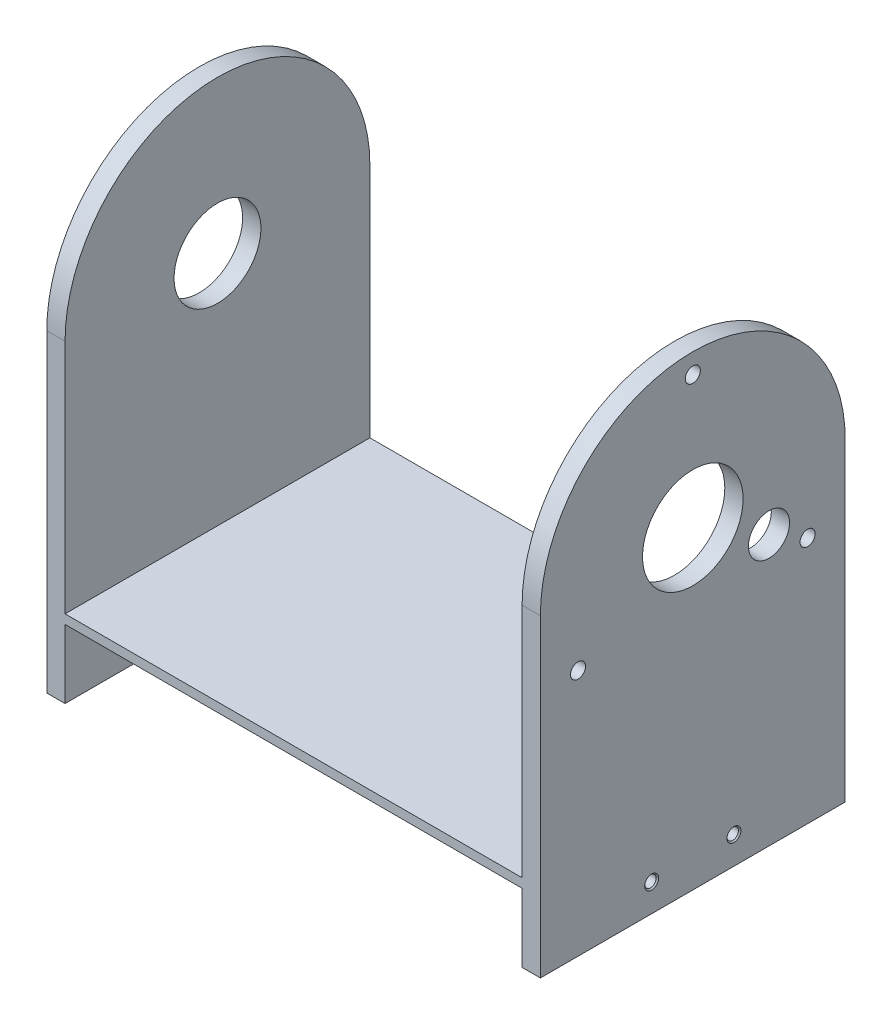
SolidWorks part; units mm, degrees
material "A-玻璃纤维"
ref_plane "前视基准面" through (0, 0, 0) normal (0, 0, 1) x (1, 0, 0)
ref_plane "上视基准面" through (0, 0, 0) normal (0, 1, 0) x (1, 0, 0)
ref_plane "右视基准面" through (0, 0, 0) normal (1, 0, 0) x (0, 0, -1)
sketch "草图1" plane through (0, 0, 0) normal (0, 1, 0) x (1, 0, 0)
  line L1 (-20, -33.35) -> (20, -33.35)
  line L2 (-20, -33.35) -> (-20, 33.35)
  line L3 (-20, 33.35) -> (20, 33.35)
  line L4 (20, -33.35) -> (20, 33.35)
  line L5 (-20, -33.35) -> (20, 33.35) construction
  line L6 (-20, 33.35) -> (20, -33.35) construction
  point P0 (0, 0)
  dimension "D1" = 40
  dimension "D2" = 66.7
extrude "凸台-拉伸1" add sketch "草图1" along normal blind 2
sketch "草图2" plane through (0, 2, 0) normal (0, 1, 0) x (1, 0, 0)
  line L0 (-20, -33.35) -> (20, -33.35) construction
  line L1 (-20, 33.35) -> (-16, 33.35)
  line L2 (-20, 33.35) -> (-20, -33.35)
  line L3 (-20, -33.35) -> (-16, -33.35)
  line L4 (-16, 33.35) -> (-16, -33.35)
  dimension "D1" = 4
extrude "凸台-拉伸2" add sketch "草图2" along normal blind 100
sketch "草图5" plane through (-20, 0, 0) normal (-1, 0, 0) x (0, 0, 1)
  line L0 (33.35, 102) -> (33.35, 0) construction
  line L1 (-33.35, 102) -> (33.35, 102) construction
  line L2 (33.35, 68.65) -> (33.35, 102)
  line L3 (33.35, 102) -> (0, 102)
  line L4 (0, 102) -> (-33.35, 102)
  line L5 (-33.35, 102) -> (-33.35, 68.65)
  circle A0 centre (0, 68.65) radius 33.35
  line M3 (33.35, 0) -> (33.35, 102)
  line M4 (33.35, 102) -> (-33.35, 102)
  line M5 (-33.35, 102) -> (-33.35, 0)
  dimension "D1" = 66.7
extrude "切除-拉伸1" cut sketch "草图5" against normal through all and the other way through all contours A0 M4 M5 | A0 M3 M4 | L2 L3 L4 L5
sketch "草图6" plane through (-20, 0, 0) normal (-1, 0, 0) x (0, 0, 1)
  line L0 (0, 68.65) -> (0, 97.65) construction
  line L1 (0, 68.65) -> (25.1147, 54.15) construction
  line L2 (0, 68.65) -> (-25.1147, 54.15) construction
  circle A0 centre (0, 68.65) radius 29 construction
  point P7 (0, 97.65)
  point P8 (25.1147, 54.15)
  point P9 (-25.1147, 54.15)
  point P10 (0, 68.65)
  dimension "D1" = 58
  dimension "D2" = 120
  dimension "D3" = 120
hole_wizard "M4 螺纹孔1" positions "草图7" profile "草图8" tap size "M4" standard "GB" end condition through all
sketch "草图7" plane through (-20, 0, 0) normal (-1, 0, 0) x (0, 0, 1)
  point P0 (0, 97.65)
  point P3 (25.1147, 54.15)
  point P6 (-25.1147, 54.15)
sketch "草图8" plane through (-20, 97.65, 0) normal (0, 1, 0) x (0, 0, 1)
  line L0 (0, 0) -> (0, 40)
  line L1 (0, 40) -> (1.65, 40)
  line L2 (1.65, 40) -> (1.65, 0.375)
  line L3 (1.65, 0.375) -> (2.025, 0)
  line L5 (2.025, 0) -> (0, 0)
  line L6 (-1.65, 0.375) -> (-2.025, 0) construction
  line L11 (0, -6.35) -> (0, 107.95) construction
  dimension "通孔螺纹孔钻头直径" = 3.3
  dimension "通孔螺纹孔钻头深度" = 40
  dimension "近端锥形沉头孔直径" = 4.05
  dimension "近端锥形沉头孔角度" = 90
sketch "草图9" plane through (0, 2, 0) normal (0, 1, 0) x (1, 0, 0)
  line L0 (-16, -33.35) -> (20, -33.35) construction
  line L1 (-11, 28.35) -> (15, 28.35) construction
  line L2 (-11, 28.35) -> (-11, -28.35) construction
  line L3 (-11, -28.35) -> (15, -28.35) construction
  line L4 (15, 28.35) -> (15, -28.35) construction
  line L5 (20, 33.35) -> (-16, 33.35) construction
  line L6 (20, -33.35) -> (20, 33.35) construction
  line L7 (-16, -33.35) -> (-16, 33.35) construction
  point P12 (-50.2188, 7.1013)
  point P13 (-11, 28.35)
  point P14 (-11, -28.35)
  point P15 (15, -28.35)
  point P16 (15, 28.35)
  dimension "D1" = 5
  dimension "D2" = 5
  dimension "D3" = 5
  dimension "D4" = 5
hole_wizard "M4 螺纹孔2" positions "草图9" profile "草图10" tap size "M4" standard "GB" end condition through all
sketch "草图10" plane through (15, 2, -28.35) normal (1, 0, 0) x (0, 0, 1)
  line L0 (0, 0) -> (0, 2)
  line L1 (0, 2) -> (1.65, 2)
  line L2 (1.65, 2) -> (1.65, 0.375)
  line L3 (1.65, 0.375) -> (2.025, 0)
  line L5 (2.025, 0) -> (0, 0)
  line L6 (-1.65, 0.375) -> (-2.025, 0) construction
  line L11 (0, -6.35) -> (0, 107.95) construction
  dimension "通孔螺纹孔钻头直径" = 3.3
  dimension "通孔螺纹孔钻头深度" = 2
  dimension "近端锥形沉头孔直径" = 4.05
  dimension "近端锥形沉头孔角度" = 90
sketch "草图11" plane through (-20, 0, 0) normal (-1, 0, 0) x (0, 0, 1)
  line L0 (-33.35, 68.65) -> (-33.35, 0) construction
  line L1 (-33.35, 17) -> (33.35, 17)
  line L2 (-33.35, 17) -> (-33.35, 15)
  line L3 (-33.35, 15) -> (33.35, 15)
  line L4 (33.35, 17) -> (33.35, 15)
  line L5 (33.35, 68.65) -> (33.35, 0) construction
  line L6 (-33.35, 0) -> (33.35, 0) construction
  dimension "D1" = 2
  dimension "D2" = 15
extrude "凸台-拉伸3" add sketch "草图11" along normal blind 100 contours L1 L4 L3 L2
ref_plane "基准面1" through (-70, 0, 0) normal (-1, 0, 0) x (0, 0, 1)
sketch "草图13" plane through (0, 0, 0) normal (0, 1, 0) x (1, 0, 0)
  line L0 (-120, -33.35) -> (-20, -33.35) construction
  line L1 (-120, 33.35) -> (-160, 33.35)
  line L2 (-120, 33.35) -> (-120, -33.35)
  line L3 (-120, -33.35) -> (-160, -33.35)
  line L4 (-160, 33.35) -> (-160, -33.35)
  dimension "D1" = 40
extrude "凸台-拉伸4" add sketch "草图13" along normal blind 2 separate body
sketch "草图14" plane through (0, 2, 0) normal (0, 1, 0) x (1, 0, 0)
  line L0 (-120, 33.35) -> (-120, -33.35) construction
  line L1 (-120, 33.35) -> (-124, 33.35)
  line L2 (-120, 33.35) -> (-120, -33.35)
  line L3 (-120, -33.35) -> (-124, -33.35)
  line L4 (-124, 33.35) -> (-124, -33.35)
  line L5 (-160, -33.35) -> (-120, -33.35) construction
  line L6 (-120, 33.35) -> (-160, 33.35) construction
  dimension "D1" = 4
extrude "凸台-拉伸5" add sketch "草图14" along normal blind 100
sketch "草图15" plane through (-124, 0, 0) normal (-1, 0, 0) x (0, 0, 1)
  line L0 (-33.35, 102) -> (33.35, 102) construction
  line L1 (33.35, 102) -> (33.35, 2) construction
  line L3 (33.35, 68.65) -> (33.35, 102)
  line L4 (33.35, 102) -> (0, 102)
  line L5 (0, 102) -> (-33.35, 102)
  line L6 (-33.35, 102) -> (-33.35, 61.9505)
  circle A0 centre (0, 68.65) radius 33.35
  line M3 (33.35, 2) -> (33.35, 102)
  line M4 (33.35, 102) -> (-33.35, 102)
  line M5 (-33.35, 102) -> (-33.35, 2)
  dimension "D1" = 66.7
extrude "切除-拉伸2" cut sketch "草图15" against normal through all and the other way through all contours A0 M4 M5 | A0 M3 M4 | L3 L4 L5 L6
sketch "草图16" plane through (0, 2, 0) normal (0, 1, 0) x (1, 0, 0)
  line L0 (-160, -33.35) -> (-124, -33.35) construction
  line L1 (-155, 28.35) -> (-129, 28.35) construction
  line L2 (-155, 28.35) -> (-155, -28.35) construction
  line L3 (-155, -28.35) -> (-129, -28.35) construction
  line L4 (-129, 28.35) -> (-129, -28.35) construction
  line L5 (-160, 33.35) -> (-160, -33.35) construction
  line L6 (-124, 33.35) -> (-160, 33.35) construction
  line L7 (-124, 33.35) -> (-124, -33.35) construction
  point P13 (-155, 28.35)
  point P14 (-155, -28.35)
  point P15 (-129, -28.35)
  point P16 (-129, 28.35)
  dimension "D1" = 5
  dimension "D2" = 5
  dimension "D3" = 5
  dimension "D4" = 5
hole_wizard "M4 螺纹孔3" positions "草图16" profile "草图17" tap size "M4" standard "GB" end condition through all
sketch "草图17" plane through (-129, 2, -28.35) normal (1, 0, 0) x (0, 0, 1)
  line L0 (0, 0) -> (0, 2)
  line L1 (0, 2) -> (1.65, 2)
  line L2 (1.65, 2) -> (1.65, 0.375)
  line L3 (1.65, 0.375) -> (2.025, 0)
  line L5 (2.025, 0) -> (0, 0)
  line L6 (-1.65, 0.375) -> (-2.025, 0) construction
  line L11 (0, -6.35) -> (0, 107.95) construction
  dimension "通孔螺纹孔钻头直径" = 3.3
  dimension "通孔螺纹孔钻头深度" = 2
  dimension "近端锥形沉头孔直径" = 4.05
  dimension "近端锥形沉头孔角度" = 90
cosmetic thread "孔螺纹线1" parameters "D2"=4
cosmetic thread "孔螺纹线2" parameters "D2"=4
cosmetic thread "孔螺纹线3" parameters "D2"=4
cosmetic thread "孔螺纹线4" parameters "D2"=4
sketch "草图18" plane through (-124, 0, 0) normal (-1, 0, 0) x (0, 0, 1)
  circle A0 centre (0, 68.65) radius 9.5
  dimension "D1" = 19
extrude "切除-拉伸3" cut sketch "草图18" against normal up to next
sketch "草图21" plane through (-16, 0, 0) normal (1, 0, 0) x (0, 0, -1)
  circle A0 centre (0, 68.65) radius 11
  dimension "D1" = 22
extrude "切除-拉伸4" cut sketch "草图21" against normal up to next
sketch "草图22" plane through (-16, 0, 0) normal (1, 0, 0) x (0, 0, -1)
  line L0 (0, 68.65) -> (25.1147, 54.15) construction
  circle A0 centre (0, 68.65) radius 19.25 construction
  circle A2 centre (16.671, 59.025) radius 4.5
  dimension "D1" = 38.5
  dimension "D2" = 9
extrude "切除-拉伸5" cut sketch "草图22" against normal up to next
fillet "圆角1" radius 2 4 edges at (20, 1, -33.35) (20, 1, 33.35) (-160, 1, 33.35) (-160, 1, -33.35)
sketch "草图23" plane through (0, 2, 0) normal (0, 1, 0) x (1, 0, 0)
  line L0 (-124, 33.35) -> (-158, 33.35) construction
  line L1 (-124, -33.35) -> (-160, -33.35)
  line L2 (-124, -33.35) -> (-124, 33.35)
  line L3 (-124, 33.35) -> (-160, 33.35)
  line L4 (-160, -33.35) -> (-160, 33.35)
  line L5 (-160, 31.35) -> (-160, -31.35) construction
extrude "切除-拉伸6" cut sketch "草图23" against normal up to next
sketch "草图24" plane through (0, 2, 0) normal (0, 1, 0) x (1, 0, 0)
  line L0 (20, -31.35) -> (20, 31.35) construction
  line L1 (-16, -33.35) -> (20, -33.35)
  line L2 (-16, -33.35) -> (-16, 33.35)
  line L3 (-16, 33.35) -> (20, 33.35)
  line L4 (20, -33.35) -> (20, 33.35)
  line L5 (18, 33.35) -> (-16, 33.35) construction
extrude "切除-拉伸7" cut sketch "草图24" against normal up to next
sketch "草图25" plane through (-16, 0, 0) normal (1, 0, 0) x (0, 0, -1)
  line L0 (0, 0) -> (0, 42.0649) construction
  line L1 (-9, 6) -> (9, 6)
  line L2 (33.35, 0) -> (-33.35, 0) construction
  point P8 (-9, 6)
  point P9 (9, 6)
  dimension "D1" = 6
  dimension "D2" = 18
hole_wizard "M3 螺纹孔1" positions "草图25" profile "草图26" tap size "M3" standard "GB" end condition through all
sketch "草图26" plane through (-16, 6, -9) normal (0, 1, 0) x (0, 0, -1)
  line L0 (0, 0) -> (0, 108)
  line L1 (0, 108) -> (1.25, 108)
  line L2 (1.25, 108) -> (1.25, 0.275)
  line L3 (1.25, 0.275) -> (1.525, 0)
  line L5 (1.525, 0) -> (0, 0)
  line L6 (-1.25, 0.275) -> (-1.525, 0) construction
  line L11 (0, -6.35) -> (0, 107.95) construction
  dimension "通孔螺纹孔钻头直径" = 2.5
  dimension "通孔螺纹孔钻头深度" = 108
  dimension "近端锥形沉头孔直径" = 3.05
  dimension "近端锥形沉头孔角度" = 90
cosmetic thread "孔螺纹线7" parameters "D2"=3
cosmetic thread "孔螺纹线8" parameters "D2"=3
